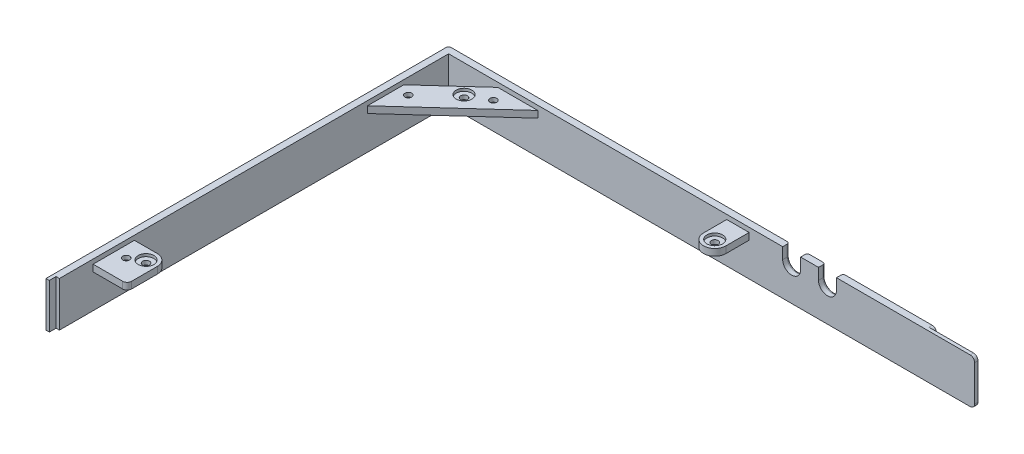
SolidWorks part; units mm, degrees
ref_plane "前视基准面" through (0, 0, 0) normal (0, 0, 1) x (1, 0, 0)
ref_plane "上视基准面" through (0, 0, 0) normal (0, 1, 0) x (1, 0, 0)
ref_plane "右视基准面" through (0, 0, 0) normal (1, 0, 0) x (0, 0, -1)
other "Configuration Table"
sketch "草图1" plane through (0, 0, 0) normal (0, 1, 0) x (1, 0, 0)
  line L0 (1.5, 0) -> (3, 0)
  line L1 (3, 0) -> (3, 173.85)
  line L2 (3, 173.85) -> (307.4, 173.85)
  line L3 (307.4, 173.85) -> (307.4, 176.85)
  line L4 (307.4, 176.85) -> (0, 176.85)
  line L5 (0, 176.85) -> (0, 0)
  line L6 (0, 0) -> (0, -3)
  line L7 (0, -3) -> (1.5, -3)
  line L8 (1.5, -3) -> (1.5, 0)
  dimension "D1" = 304.4
  dimension "D2" = 173.85
  dimension "D3" = 3
  dimension "D4" = 3
  dimension "D5" = 3
extrude "凸台-拉伸1" add sketch "草图1" along normal blind 20
ref_plane "基准面1" through (0, 14, 0) normal (0, 1, 0) x (1, 0, 0)
sketch "草图2" plane through (0, 14, 0) normal (0, 1, 0) x (1, 0, 0)
  line L0 (307.4, -177.55) -> (307.4, -138.0563) construction
  line L1 (3, 173.85) -> (611.8, 173.85) construction
  line L2 (3, 173.85) -> (3, -181.25) construction
  line L3 (3, -181.25) -> (611.8, -181.25) construction
  line L4 (611.8, 173.85) -> (611.8, -181.25) construction
  line L5 (611.8, 0) -> (505.4057, 0) construction
  line L6 (3, 153.85) -> (25, 173.85)
  line L7 (42.8393, 173.85) -> (3, 137.6325)
  line L8 (3, 173.85) -> (307.4, 173.85) construction
  line L9 (3, 0) -> (3, 173.85) construction
  line L10 (42.8393, 173.85) -> (25, 173.85)
  line L11 (3, 137.6325) -> (3, 153.85)
  line L12 (137.25, 163.5) -> (137.25, 173.85)
  line L13 (127.25, 163.5) -> (127.25, 173.85)
  line L14 (127.25, 173.85) -> (137.25, 173.85)
  line L16 (3, 23.8703) -> (3, 33.5)
  line L17 (3, 33.5) -> (13.2, 33.5)
  line L18 (18.2, 28.5) -> (18.2, 15.044)
  line L19 (18.2, 15.044) -> (3, 15.044)
  line L20 (3, 15.044) -> (3, 23.8703)
  circle A0 centre (20.25, 163.5) radius 1.525
  circle A1 centre (132.25, 163.5) radius 1.525
  arc A2 (127.25, 163.5) -> (137.25, 163.5) centre (132.25, 163.5) ccw
  circle A3 centre (13.2, 28.5) radius 1.525
  arc A4 (18.2, 28.5) -> (13.2, 33.5) centre (13.2, 28.5) ccw
  dimension "D3" = 3.05
  dimension "D9" = 3.05
  dimension "D10" = 10
  dimension "D13" = 3.05
  dimension "D15" = 10
  dimension "D1" = 608.8
  dimension "D2" = 355.1
  dimension "D4" = 287.15
  dimension "D5" = 163.5
  dimension "D6" = 22
  dimension "D7" = 20
  dimension "D8" = 12
  dimension "D11" = 163.5
  dimension "D12" = 175.15
  dimension "D14" = 28.5
  dimension "D16" = 294.2
  dimension "D17" = 173.85
extrude "凸台-拉伸2" add sketch "草图2" along normal blind 3 from offset 1
sketch "草图3" plane through (0, 0, -176.85) normal (0, 0, -1) x (-1, 0, 0)
  line L0 (-276.4, 10.5) -> (-307.4, 10.5)
  line L1 (-307.4, 0) -> (0, 0) construction
  line L2 (-307.4, 20) -> (-307.4, 0) construction
  line L3 (-276.4, 10.5) -> (-276.4, 20)
  line L4 (-307.4, 20) -> (0, 20) construction
  line L5 (-276.4, 20) -> (-307.4, 20)
  line L6 (-307.4, 20) -> (-307.4, 10.5)
  dimension "D1" = 10.5
  dimension "D2" = 31
extrude "切除-拉伸1" cut sketch "草图3" against normal up to next
ref_plane "基准面2" through (317.4, 0, 0) normal (1, 0, 0) x (0, 0, -1)
sketch "草图4" plane through (0, 18, 0) normal (0, 1, 0) x (1, 0, 0)
  circle A0 centre (13.2, 28.5) radius 3.5
  circle A1 centre (20.25, 163.5) radius 3.5
  circle A2 centre (132.25, 163.5) radius 3.5
  dimension "D1" = 7
  dimension "D2" = 7
  dimension "D3" = 7
extrude "切除-拉伸2" cut sketch "草图4" against normal blind 1.2
sketch "草图5" plane through (0, 15, 0) normal (0, -1, 0) x (1, 0, 0)
  line L0 (132.25, -163.5) -> (132.25, -166.8465) construction
  line L1 (3, -173.85) -> (307.4, -173.85) construction
  line L2 (132.25, -167.85) -> (75.3924, -167.85) construction
  line L3 (3, 0) -> (3, -173.85) construction
  line L4 (13.2, -28.5) -> (9.8492, -28.5) construction
  line L5 (8, -28.5) -> (8, -37.2968) construction
  line L6 (3, -33.5) -> (3, -15.044) construction
  line L7 (3, -173.85) -> (276.4, -173.85) construction
  circle A1 centre (29, -167.85) radius 1.525
  circle A3 centre (8, -150.85) radius 1.525
  circle A4 centre (8, -24.8) radius 1.525
  dimension "D3" = 3.05
  dimension "D5" = 3.05
  dimension "D7" = 3.05
  dimension "D4" = 26
  dimension "D6" = 149.05
  dimension "D8" = 23
extrude "切除-拉伸3" cut sketch "草图5" against normal up to next
fillet "圆角1" radius 1 1 edges at (0, 10, -176.85)
fillet "圆角3" radius 1 1 edges at (276.4, 10.5, -175.35)
sketch "草图6" plane through (0, 15, 0) normal (0, -1, 0) x (1, 0, 0)
  circle A0 centre (8, -24.8) radius 3.5
  circle A1 centre (8, -150.85) radius 3.5
  circle A2 centre (29, -167.85) radius 3.5
  dimension "D1" = 7
  dimension "D2" = 7
  dimension "D3" = 7
extrude "切除-拉伸4" cut sketch "草图6" against normal blind 1.2
sketch "草图7" plane through (0, 0, -176.85) normal (0, 0, -1) x (-1, 0, 0)
  line L0 (0, 20) -> (0, 0) construction
  line L2 (-276.4, 20) -> (-1, 20) construction
  line L4 (-238, 0) -> (-307.4, 0)
  line L5 (-238, 0) -> (-238, 20)
  line L6 (-238, 20) -> (-307.4, 20)
  line L7 (-307.4, 0) -> (-307.4, 20)
  dimension "D1" = 238
extrude "切除-拉伸5" cut sketch "草图7" against normal blind 3
sketch "草图8" plane through (0, 0, -176.85) normal (0, 0, -1) x (-1, 0, 0)
  line L0 (-238, 0) -> (-1, 0) construction
  line L1 (-238, 20) -> (-218, 20)
  line L2 (-238, 20) -> (-238, 0)
  line L3 (-238, 0) -> (-218, 0)
  line L4 (-218, 20) -> (-218, 0)
  dimension "D1" = 20
extrude "切除-拉伸6" cut sketch "草图8" against normal blind 1.5
fillet "圆角4" radius 2 2 edges at (218, 20, -176.1) (218, 0, -176.1)
fillet "圆角5" radius 2 2 edges at (238, 20, -174.6) (238, 0, -174.6)
fillet "圆角6" radius 2 1 edges at (18.2, 16.5, -15.044)
sketch "草图9" plane through (0, 0, -173.85) normal (0, 0, 1) x (1, 0, 0)
  line L1 (3, 20) -> (236, 20) construction
  line L3 (152.25, 15) -> (152.25, 20)
  line L4 (152.25, 20) -> (160.25, 20)
  line L5 (160.25, 15) -> (160.25, 20)
  line L6 (137.25, 18) -> (137.25, 15) construction
  line L7 (168.25, 15) -> (168.25, 20)
  line L8 (168.25, 20) -> (176.25, 20)
  line L9 (176.25, 15) -> (176.25, 20)
  arc A0 (152.25, 15) -> (160.25, 15) centre (156.25, 15) ccw
  arc A1 (168.25, 15) -> (176.25, 15) centre (172.25, 15) ccw
  dimension "D1" = 8
  dimension "D3" = 8
  dimension "D5" = 5
  dimension "D2" = 15
  dimension "D4" = 0
  dimension "D6" = 5
extrude "切除-拉伸7" cut sketch "草图9" against normal blind 10
fillet "圆角7" radius 1 3 edges at (160.25, 17.5, -176.85) (156.25, 11, -176.85) (152.25, 17.5, -176.85)
fillet "圆角8" radius 1 3 edges at (176.25, 17.5, -176.85) (172.25, 11, -176.85) (168.25, 17.5, -176.85)
